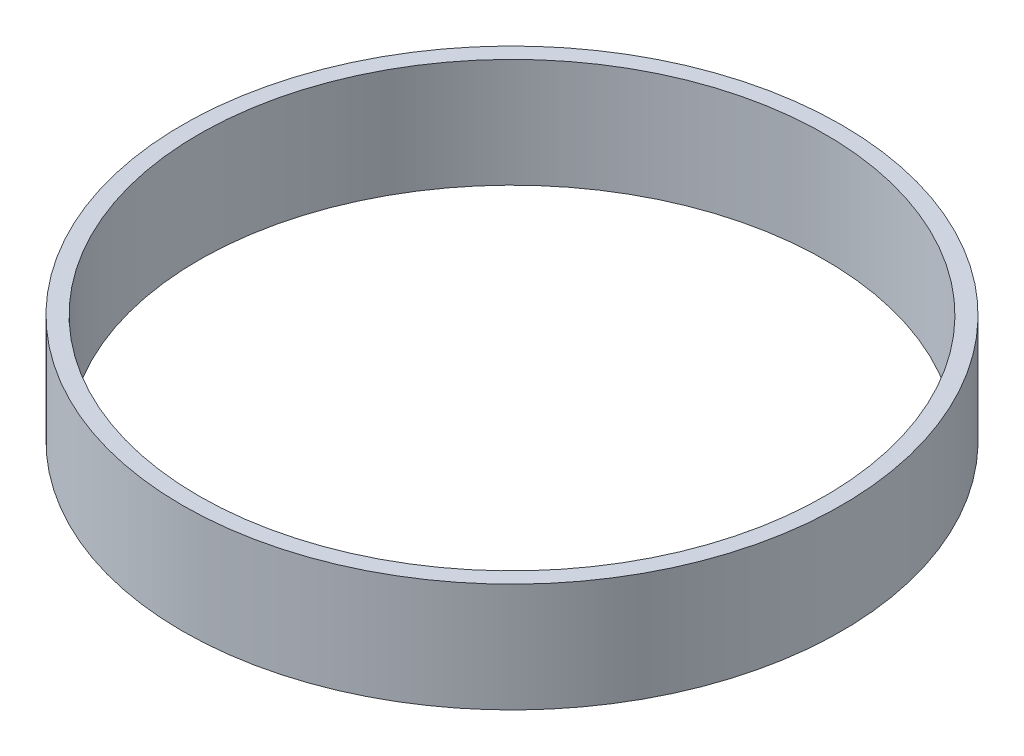
SolidWorks part; units mm, degrees
ref_plane "Front Plane" through (0, 0, 0) normal (0, 0, 1) x (1, 0, 0)
ref_plane "Top Plane" through (0, 0, 0) normal (0, 1, 0) x (1, 0, 0)
ref_plane "Right Plane" through (0, 0, 0) normal (1, 0, 0) x (0, 0, -1)
sketch "Base" plane through (0, 0, 0) normal (0, 1, 0) x (1, 0, 0)
  circle A0 centre (0, 0) radius 115
  circle A1 centre (0, 0) radius 121
  dimension "D1" = 230
  dimension "D2" = 6
extrude "Base-Extrude" add sketch "Base" along normal blind 40
hole_wizard "CSK for M5 Countersunk Raised Head Screw1" positions "Sketch1" profile "Sketch2" countersink size "M5" standard "ISO"
sketch "Sketch1" plane through (37.9687, -4, -14.4349) normal (0, -1, 0) x (-1, 0, 0)
  circle A0 centre (37.9687, -14.4349) radius 118
  point P28 (-80.0313, -14.4349)
  point P38 (-45.4699, 69.0037)
  point P39 (37.9687, 103.5651)
  point P40 (121.4073, 69.0037)
  point P41 (155.9687, -14.4349)
  point P42 (121.4073, -97.8735)
  point P43 (37.9687, -132.4349)
  point P44 (-45.4699, -97.8735)
sketch "Sketch2" plane through (83.4386, -4, 83.4386) normal (1, 0, 0) x (0, 0, -1)
  line L0 (0, 0) -> (0, 21.6524)
  line L1 (0, 21.6524) -> (2.75, 20)
  line L2 (2.75, 20) -> (2.75, 2.45)
  line L3 (2.75, 2.45) -> (5.2, 0)
  line L4 (5.2, 0) -> (0, 0)
  line L5 (-2.75, 2.45) -> (-5.2, 0) construction
  line L6 (0, 21.6524) -> (-2.75, 20) construction
  line L7 (0, -6.35) -> (0, 107.95) construction
  dimension "Hole Dia." = 5.5
  dimension "Hole Depth" = 20
  dimension "Near C'Sink Dia." = 10.4
  dimension "Near C'Sink Angle" = 90
  dimension "Drill Angle" = 118
equation "\"inner radius\"= 230"
equation "\"wall thickness\"= 6\t"
equation "\"outer radius\"= \"inner radius\" + 2 * \"wall thickness\""
equation "\"D2@Base\"=\"wall thickness\""
equation "\"D1@Base\"=\"inner radius\""
equation "\"height\" = 40"
equation "\"D1@Base-Extrude\"=\"height\""
equation "\"wheel distance\" = 100"
